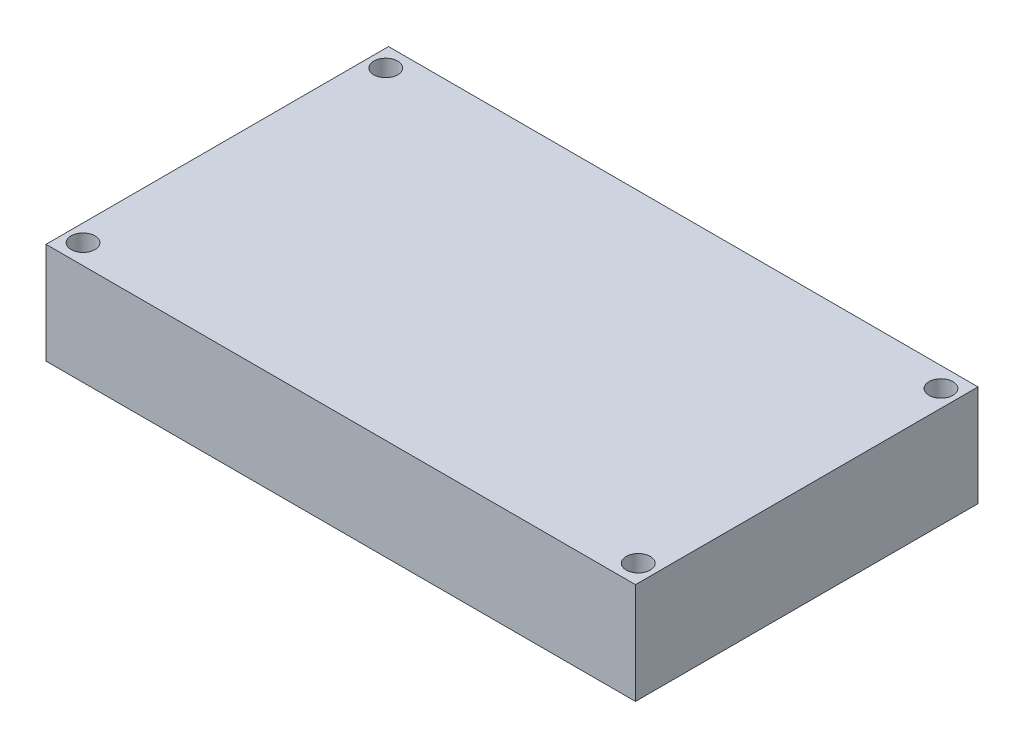
SolidWorks part; units mm, degrees
ref_plane "Front Plane" through (0, 0, 0) normal (0, 0, 1) x (1, 0, 0)
ref_plane "Top Plane" through (0, 0, 0) normal (0, 1, 0) x (1, 0, 0)
ref_plane "Right Plane" through (0, 0, 0) normal (1, 0, 0) x (0, 0, -1)
sketch "Sketch1" plane through (0, 0, 0) normal (0, 1, 0) x (1, 0, 0)
  line L0 (0, 43) -> (74, 0) construction
  line L1 (0, 0) -> (74, 0)
  line L2 (0, 0) -> (0, 43)
  line L3 (0, 43) -> (74, 43)
  line L4 (74, 0) -> (74, 43)
  line L6 (2.15, 40.5) -> (71.85, 40.5) construction
  line L7 (2.15, 40.5) -> (2.15, 2.5) construction
  line L8 (2.15, 2.5) -> (71.85, 2.5) construction
  line L9 (71.85, 40.5) -> (71.85, 2.5) construction
  line L10 (2.15, 40.5) -> (71.85, 2.5) construction
  line L11 (2.15, 2.5) -> (71.85, 40.5) construction
  circle A0 centre (2.15, 40.5) radius 1.5
  circle A1 centre (71.85, 40.5) radius 1.5
  circle A2 centre (71.85, 2.5) radius 1.5
  circle A3 centre (2.15, 2.5) radius 1.5
  point P5 (37, 21.5)
  dimension "D3" = 3
  dimension "D1" = 74
  dimension "D2" = 43
  dimension "D4" = 38
  dimension "D5" = 69.7
extrude "Boss-Extrude1" add sketch "Sketch1" along normal blind 12.7
